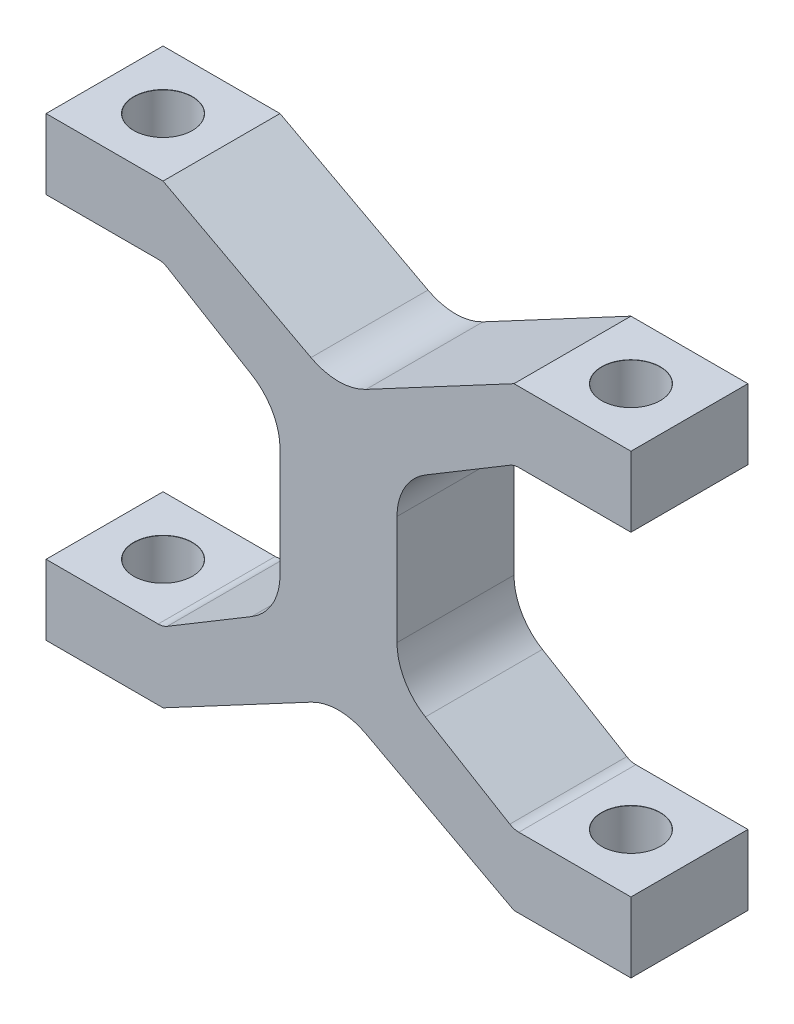
SolidWorks part; units mm, degrees
material "AISI 1045 Steel, cold drawn"
ref_plane "Front Plane" through (0, 0, 0) normal (0, 0, 1) x (1, 0, 0)
ref_plane "Top Plane" through (0, 0, 0) normal (0, 1, 0) x (1, 0, 0)
ref_plane "Right Plane" through (0, 0, 0) normal (1, 0, 0) x (0, 0, -1)
sketch "Sketch1" plane through (0, 0, 0) normal (0, 0, 1) x (1, 0, 0)
  line L0 (-69.9325, 0) -> (80.8832, 0) construction
  line L3 (-50, 27) -> (-50, 39)
  line L4 (-50, 39) -> (-30, 39)
  line L5 (-30, 39) -> (0, 23)
  line L6 (0, 122.3294) -> (0, -36.7286) construction
  line L20 (-50, 27) -> (-30, 27)
  line L21 (-30, 27) -> (-10, 15)
  line L22 (-10, 15) -> (-10, -15)
  line L23 (10, 15) -> (10, -15)
  line L24 (30, 27) -> (10, 15)
  line L25 (50, 27) -> (30, 27)
  line L26 (50, 27) -> (50, 39)
  line L27 (30, 39) -> (0, 23)
  line L28 (50, 39) -> (30, 39)
  line L29 (50, -39) -> (30, -39)
  line L30 (30, -39) -> (0, -23)
  line L31 (50, -27) -> (50, -39)
  line L32 (50, -27) -> (30, -27)
  line L33 (30, -27) -> (10, -15)
  line L34 (-30, -27) -> (-10, -15)
  line L35 (-50, -27) -> (-30, -27)
  line L36 (-30, -39) -> (0, -23)
  line L37 (-50, -39) -> (-30, -39)
  line L38 (-50, -27) -> (-50, -39)
  point P26 (10, 0)
  point P27 (-10, 0)
  dimension "D1" = 15
  dimension "D2" = 100
  dimension "D3" = 12
  dimension "D4" = 20
  dimension "D5" = 78
  dimension "D6" = 20
  dimension "D7" = 23
extrude "Boss-Extrude1" add sketch "Sketch1" along normal mid plane 20
fillet "Fillet1" radius 10 6 edges at (0, -23, 0) (0, 23, 0) (10, -15, 0) (10, 15, 0) (-10, -15, 0) (-10, 15, 0)
hole_wizard "Ø10.0mm Dowel Hole1" positions "3DSketch2" profile "Sketch3" hole size "Ø10.0" standard "ISO"
sketch3d "3DSketch2"
  line L0 (-30, 39, -10) -> (-50, 39, -10) construction
  line L1 (-50, 39, 10) -> (-50, 39, -10) construction
  line L2 (-30, -27, -10) -> (-50, -27, -10) construction
  line L3 (-50, -27, 10) -> (-50, -27, -10) construction
  line L4 (50, 39, -10) -> (30, 39, -10) construction
  line L5 (50, 39, 10) -> (50, 39, -10) construction
  line L6 (50, -27, -10) -> (30, -27, -10) construction
  line L7 (50, -27, 10) -> (50, -27, -10) construction
  point P0 (-40, 39, 0)
  point P2 (-40, -27, 0)
  point P4 (40, 39, 0)
  point P6 (40, -27, 0)
  point P11 (-40, 39, -10)
  point P14 (-50, 39, 0)
  point P17 (-40, -27, -10)
  point P20 (-50, -27, 0)
  point P23 (40, 39, -10)
  point P26 (50, 39, 0)
  point P29 (40, -27, -10)
  point P32 (50, -27, 0)
sketch "Sketch3" plane through (-40, 39, 0) normal (1, 0, 0) x (0, 0, 1)
  line L0 (0, 0) -> (0, 27.5043)
  line L1 (0, 27.5043) -> (5, 24.5)
  line L2 (5, 24.5) -> (5, 0.025)
  line L3 (5, 0.025) -> (5.025, 0)
  line L5 (5.025, 0) -> (0, 0)
  line L6 (-5, 0.025) -> (-5.025, 0) construction
  line L10 (0, 27.5043) -> (-5, 24.5) construction
  line L11 (0, -6.35) -> (0, 107.95) construction
  dimension "Hole Dia." = 10
  dimension "Hole Depth" = 24.5
  dimension "Near C'Sink Dia." = 10.05
  dimension "Near C'Sink Angle" = 90
  dimension "Drill Angle" = 118
fillet "Fillet2" radius 3 4 edges at (-30, 27, 0) (30, 27, 0) (-30, -27, 0) (30, -27, 0)
